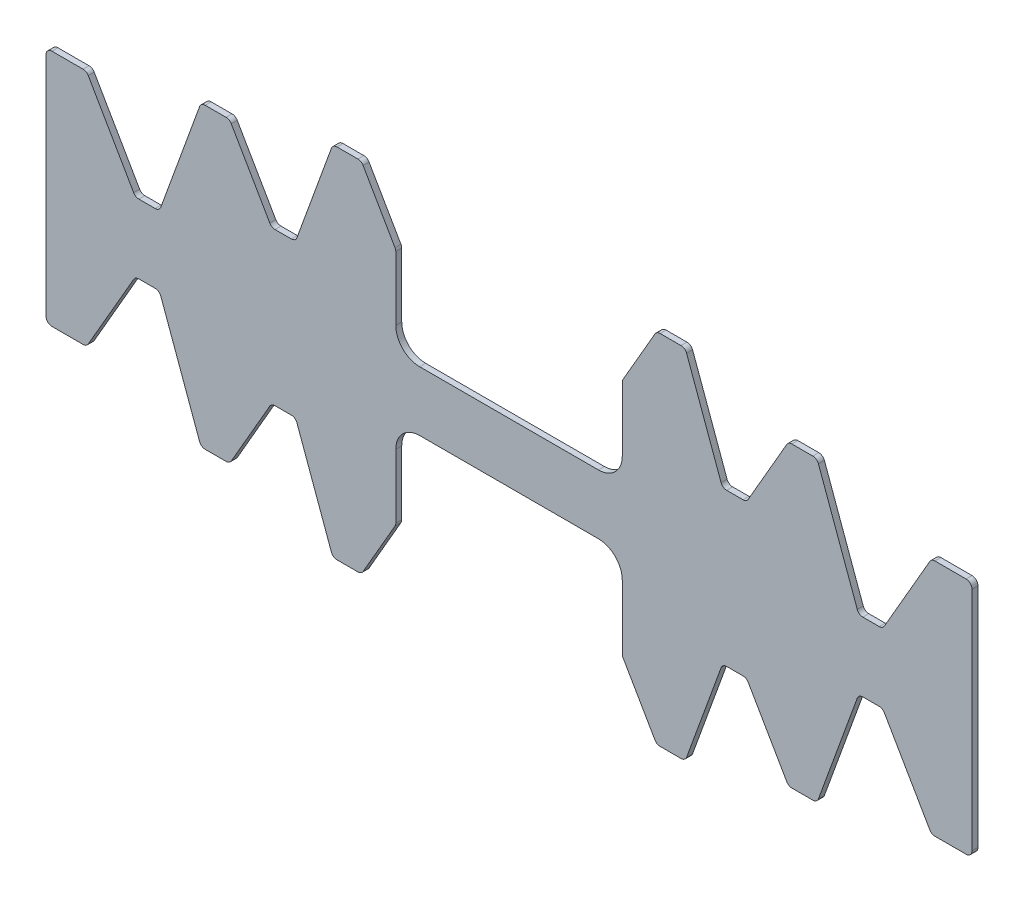
SolidWorks part; units mm, degrees
ref_plane "Front Plane" through (0, 0, 0) normal (0, 0, 1) x (1, 0, 0)
ref_plane "Top Plane" through (0, 0, 0) normal (0, 1, 0) x (1, 0, 0)
ref_plane "Right Plane" through (0, 0, 0) normal (1, 0, 0) x (0, 0, -1)
sketch "Model" plane through (0, 0, 0) normal (0, 0, 1) x (1, 0, 0)
  line L0 (1535.0491, 341.2728) -> (1533.2943, 341.2728)
  line L1 (1532.8613, 341.5228) -> (1530.1859, 346.1568)
  line L2 (1530.1189, 346.4068) -> (1530.1189, 351.7728)
  line L3 (1513.1189, 353.7728) -> (1528.1189, 353.7728)
  line L4 (1511.1189, 346.4068) -> (1511.1189, 351.7728)
  line L5 (1508.3765, 341.5228) -> (1511.0519, 346.1568)
  line L6 (1506.1887, 341.2728) -> (1507.9435, 341.2728)
  line L7 (1505.7188, 341.6018) -> (1502.8282, 349.5438)
  line L8 (1502.3583, 349.8728) -> (1500.9848, 349.8728)
  line L9 (1497.3186, 344.0228) -> (1500.5518, 349.6228)
  line L10 (1495.1308, 343.7728) -> (1496.8856, 343.7728)
  line L11 (1494.661, 344.1018) -> (1491.4063, 353.0438)
  line L12 (1490.9365, 353.3728) -> (1489.563, 353.3728)
  line L13 (1485.3195, 346.5228) -> (1489.13, 353.1228)
  line L14 (1482.2751, 346.2728) -> (1484.8865, 346.2728)
  line L15 (1481.7751, 346.7728) -> (1481.7751, 365.7728)
  line L16 (1482.2751, 366.2728) -> (1484.8865, 366.2728)
  line L17 (1485.3195, 366.0228) -> (1489.13, 359.4228)
  line L18 (1490.9365, 359.1728) -> (1489.563, 359.1728)
  line L19 (1494.661, 368.4438) -> (1491.4063, 359.5018)
  line L20 (1495.1308, 368.7728) -> (1496.8856, 368.7728)
  line L21 (1497.3186, 368.5228) -> (1500.5518, 362.9228)
  line L22 (1502.3583, 362.6728) -> (1500.9848, 362.6728)
  line L23 (1505.7188, 370.9438) -> (1502.8282, 363.0018)
  line L24 (1506.1887, 371.2728) -> (1507.9435, 371.2728)
  line L25 (1508.3765, 371.0228) -> (1511.0519, 366.3888)
  line L26 (1511.1189, 366.1388) -> (1511.1189, 360.7728)
  line L27 (1513.1189, 358.7728) -> (1528.1189, 358.7728)
  line L28 (1530.1189, 366.1388) -> (1530.1189, 360.7728)
  line L29 (1532.8613, 371.0228) -> (1530.1859, 366.3888)
  line L30 (1535.0491, 371.2728) -> (1533.2943, 371.2728)
  line L31 (1535.519, 370.9438) -> (1538.4096, 363.0018)
  line L32 (1538.8795, 362.6728) -> (1540.253, 362.6728)
  line L33 (1543.9192, 368.5228) -> (1540.686, 362.9228)
  line L34 (1546.107, 368.7728) -> (1544.3522, 368.7728)
  line L35 (1546.5768, 368.4438) -> (1549.8315, 359.5018)
  line L36 (1550.3013, 359.1728) -> (1551.6748, 359.1728)
  line L37 (1555.9183, 366.0228) -> (1552.1078, 359.4228)
  line L38 (1558.9627, 366.2728) -> (1556.3513, 366.2728)
  line L39 (1559.4627, 346.7728) -> (1559.4627, 365.7728)
  line L40 (1558.9627, 346.2728) -> (1556.3513, 346.2728)
  line L41 (1555.9183, 346.5228) -> (1552.1078, 353.1228)
  line L42 (1550.3013, 353.3728) -> (1551.6748, 353.3728)
  line L43 (1546.5768, 344.1018) -> (1549.8315, 353.0438)
  line L44 (1546.107, 343.7728) -> (1544.3522, 343.7728)
  line L45 (1543.9192, 344.0228) -> (1540.686, 349.6228)
  line L46 (1538.8795, 349.8728) -> (1540.253, 349.8728)
  line L47 (1535.519, 341.6018) -> (1538.4096, 349.5438)
  arc A0 (1535.0491, 341.2728) -> (1535.519, 341.6018) centre (1535.0491, 341.7728) ccw
  arc A1 (1532.8613, 341.5228) -> (1533.2943, 341.2728) centre (1533.2943, 341.7728) ccw
  arc A2 (1530.1189, 346.4068) -> (1530.1859, 346.1568) centre (1530.6189, 346.4068) ccw
  arc A3 (1530.1189, 351.7728) -> (1528.1189, 353.7728) centre (1528.1189, 351.7728) ccw
  arc A4 (1513.1189, 353.7728) -> (1511.1189, 351.7728) centre (1513.1189, 351.7728) ccw
  arc A5 (1511.0519, 346.1568) -> (1511.1189, 346.4068) centre (1510.6189, 346.4068) ccw
  arc A6 (1507.9435, 341.2728) -> (1508.3765, 341.5228) centre (1507.9435, 341.7728) ccw
  arc A7 (1505.7188, 341.6018) -> (1506.1887, 341.2728) centre (1506.1887, 341.7728) ccw
  arc A8 (1502.8282, 349.5438) -> (1502.3583, 349.8728) centre (1502.3583, 349.3728) ccw
  arc A9 (1500.9848, 349.8728) -> (1500.5518, 349.6228) centre (1500.9848, 349.3728) ccw
  arc A10 (1496.8856, 343.7728) -> (1497.3186, 344.0228) centre (1496.8856, 344.2728) ccw
  arc A11 (1494.661, 344.1018) -> (1495.1308, 343.7728) centre (1495.1308, 344.2728) ccw
  arc A12 (1491.4063, 353.0438) -> (1490.9365, 353.3728) centre (1490.9365, 352.8728) ccw
  arc A13 (1489.563, 353.3728) -> (1489.13, 353.1228) centre (1489.563, 352.8728) ccw
  arc A14 (1484.8865, 346.2728) -> (1485.3195, 346.5228) centre (1484.8865, 346.7728) ccw
  arc A15 (1481.7751, 346.7728) -> (1482.2751, 346.2728) centre (1482.2751, 346.7728) ccw
  arc A16 (1482.2751, 366.2728) -> (1481.7751, 365.7728) centre (1482.2751, 365.7728) ccw
  arc A17 (1485.3195, 366.0228) -> (1484.8865, 366.2728) centre (1484.8865, 365.7728) ccw
  arc A18 (1489.13, 359.4228) -> (1489.563, 359.1728) centre (1489.563, 359.6728) ccw
  arc A19 (1490.9365, 359.1728) -> (1491.4063, 359.5018) centre (1490.9365, 359.6728) ccw
  arc A20 (1495.1308, 368.7728) -> (1494.661, 368.4438) centre (1495.1308, 368.2728) ccw
  arc A21 (1497.3186, 368.5228) -> (1496.8856, 368.7728) centre (1496.8856, 368.2728) ccw
  arc A22 (1500.5518, 362.9228) -> (1500.9848, 362.6728) centre (1500.9848, 363.1728) ccw
  arc A23 (1502.3583, 362.6728) -> (1502.8282, 363.0018) centre (1502.3583, 363.1728) ccw
  arc A24 (1506.1887, 371.2728) -> (1505.7188, 370.9438) centre (1506.1887, 370.7728) ccw
  arc A25 (1508.3765, 371.0228) -> (1507.9435, 371.2728) centre (1507.9435, 370.7728) ccw
  arc A26 (1511.1189, 366.1388) -> (1511.0519, 366.3888) centre (1510.6189, 366.1388) ccw
  arc A27 (1511.1189, 360.7728) -> (1513.1189, 358.7728) centre (1513.1189, 360.7728) ccw
  arc A28 (1528.1189, 358.7728) -> (1530.1189, 360.7728) centre (1528.1189, 360.7728) ccw
  arc A29 (1530.1859, 366.3888) -> (1530.1189, 366.1388) centre (1530.6189, 366.1388) ccw
  arc A30 (1533.2943, 371.2728) -> (1532.8613, 371.0228) centre (1533.2943, 370.7728) ccw
  arc A31 (1535.519, 370.9438) -> (1535.0491, 371.2728) centre (1535.0491, 370.7728) ccw
  arc A32 (1538.4096, 363.0018) -> (1538.8795, 362.6728) centre (1538.8795, 363.1728) ccw
  arc A33 (1540.253, 362.6728) -> (1540.686, 362.9228) centre (1540.253, 363.1728) ccw
  arc A34 (1544.3522, 368.7728) -> (1543.9192, 368.5228) centre (1544.3522, 368.2728) ccw
  arc A35 (1546.5768, 368.4438) -> (1546.107, 368.7728) centre (1546.107, 368.2728) ccw
  arc A36 (1549.8315, 359.5018) -> (1550.3013, 359.1728) centre (1550.3013, 359.6728) ccw
  arc A37 (1551.6748, 359.1728) -> (1552.1078, 359.4228) centre (1551.6748, 359.6728) ccw
  arc A38 (1556.3513, 366.2728) -> (1555.9183, 366.0228) centre (1556.3513, 365.7728) ccw
  arc A39 (1559.4627, 365.7728) -> (1558.9627, 366.2728) centre (1558.9627, 365.7728) ccw
  arc A40 (1558.9627, 346.2728) -> (1559.4627, 346.7728) centre (1558.9627, 346.7728) ccw
  arc A41 (1555.9183, 346.5228) -> (1556.3513, 346.2728) centre (1556.3513, 346.7728) ccw
  arc A42 (1552.1078, 353.1228) -> (1551.6748, 353.3728) centre (1551.6748, 352.8728) ccw
  arc A43 (1550.3013, 353.3728) -> (1549.8315, 353.0438) centre (1550.3013, 352.8728) ccw
  arc A44 (1546.107, 343.7728) -> (1546.5768, 344.1018) centre (1546.107, 344.2728) ccw
  arc A45 (1543.9192, 344.0228) -> (1544.3522, 343.7728) centre (1544.3522, 344.2728) ccw
  arc A46 (1540.686, 349.6228) -> (1540.253, 349.8728) centre (1540.253, 349.3728) ccw
  arc A47 (1538.8795, 349.8728) -> (1538.4096, 349.5438) centre (1538.8795, 349.3728) ccw
extrude "Boss-Extrude1" add sketch "Model" along normal blind 0.5 contours L20 A21 L21 A22 L22 A23 L23 A24 L24 A25 L25 A26 L26 A27 L27 A28 L28 A29 L29 A30 L30 A31 L31 A32 L32 A33 L33 A34 L34 A35 L35 A36 L36 A37 L37 A38 L38 A39 L39 A40 L40 A41 L41 A42 L42 A43 L43 A44 L44 A45 L45 A46 L46 A47 L47 A0 L0 A1 L1 A2 L2 A3 L3 A4 L4 A5 L5 A6 L6 A7 L7 A8 L8 A9 L9 A10 L10 A11 L11 A12 L12 A13 L13 A14 L14 A15 L15 A16 L16 A17 L17 A18 L18 A19 L19 A20
